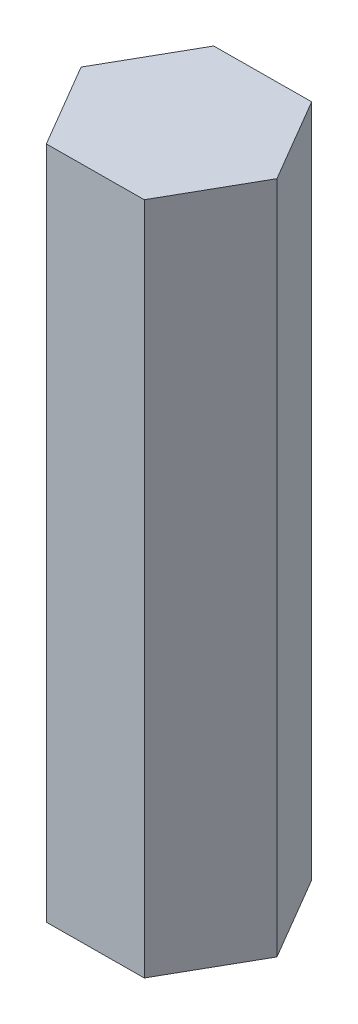
SolidWorks part; units mm, degrees
ref_plane "Front Plane" through (0, 0, 0) normal (0, 0, 1) x (1, 0, 0)
ref_plane "Top Plane" through (0, 0, 0) normal (0, 1, 0) x (1, 0, 0)
ref_plane "Right Plane" through (0, 0, 0) normal (1, 0, 0) x (0, 0, -1)
sketch "Sketch1" plane through (0, 0, 0) normal (0, 1, 0) x (1, 0, 0)
  line L1 (3.6244, 6.3739) -> (-3.7078, 6.3258)
  line L2 (-3.7078, 6.3258) -> (-7.3322, -0.0481)
  line L3 (-7.3322, -0.0481) -> (-3.6244, -6.3739)
  line L4 (-3.6244, -6.3739) -> (3.7078, -6.3258)
  line L5 (3.7078, -6.3258) -> (7.3322, 0.0481)
  line L6 (7.3322, 0.0481) -> (3.6244, 6.3739)
  circle A0 centre (0, 0) radius 6.35 construction
  dimension "D1" = 12.7
extrude "Boss-Extrude1" add sketch "Sketch1" along normal blind 50.8
